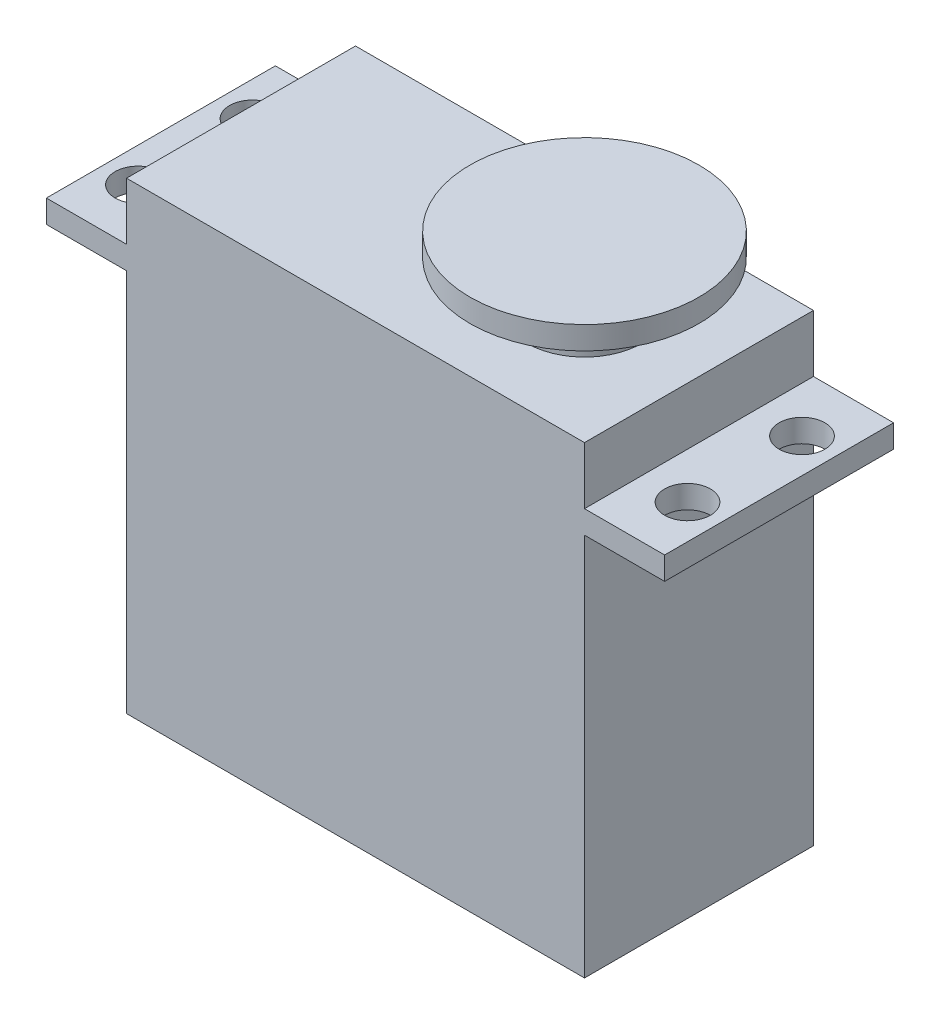
SolidWorks part; units mm, degrees
ref_plane "Front Plane" through (0, 0, 0) normal (0, 0, 1) x (1, 0, 0)
ref_plane "Top Plane" through (0, 0, 0) normal (0, 1, 0) x (1, 0, 0)
ref_plane "Right Plane" through (0, 0, 0) normal (1, 0, 0) x (0, 0, -1)
sketch "Sketch1" plane through (0, 0, 0) normal (0, 0, 1) x (1, 0, 0)
  line L1 (0, 0) -> (40, 0)
  line L2 (0, 0) -> (0, 40.5)
  line L3 (0, 40.5) -> (40, 40.5)
  line L4 (40, 0) -> (40, 40.5)
  dimension "D1" = 40.5
  dimension "D2" = 40
extrude "Boss-Extrude1" add sketch "Sketch1" along normal blind 20
sketch "Sketch2" plane through (0, 40.5, 0) normal (0, 1, 0) x (1, 0, 0)
  line L0 (40, -20) -> (40, 0) construction
  circle A0 centre (30, -10) radius 10
  dimension "D1" = 20
extrude "Boss-Extrude2" add sketch "Sketch2" along normal blind 6
sketch "Sketch3" plane through (0, 0, 0) normal (0, -1, 0) x (-1, 0, 0)
  line L1 (0, -20) -> (0, 0) construction
  line L2 (0, -20) -> (-40, -20) construction
  circle A0 centre (-17.5, -2.5) radius 1
  circle A1 centre (-17.5, -17.5) radius 1
  circle A2 centre (-2.5, -17.5) radius 1
  circle A3 centre (-2.5, -2.5) radius 1
  dimension "D3" = 2
  dimension "D4" = 2.5
  dimension "D1" = 15
  dimension "D2" = 15
  dimension "D5" = 2.5
sketch "Sketch4" plane through (0, 40.5, 0) normal (0, 1, 0) x (1, 0, 0)
  line L0 (9.5, -17) -> (9.5, -3) construction
  line L1 (0, -20) -> (0, 0) construction
  line L2 (30, 0) -> (0, 0) construction
  circle A0 centre (2.5, -10) radius 1.0762
  circle A1 centre (9.5, -17) radius 1.0762
  circle A2 centre (9.5, -3) radius 1.0762
  dimension "D4" = 2.5
  dimension "D5" = 3
  dimension "D1" = 14
  dimension "D2" = 7
  dimension "D3" = 7
sketch "Sketch5" plane through (0, 40.5, 0) normal (0, 1, 0) x (1, 0, 0)
  circle A0 centre (30, -10) radius 10
  circle A1 centre (30, -10) radius 5
  dimension "D1" = 10
extrude "Cut-Extrude3" cut sketch "Sketch5" along normal blind 4
sketch "Sketch6" plane through (0, 0, 0) normal (-1, 0, 0) x (0, 0, 1)
  line L0 (20, 40.5) -> (20, 0) construction
  line L1 (20, 35.5) -> (0, 35.5)
  line L2 (20, 35.5) -> (20, 33.5)
  line L3 (20, 33.5) -> (0, 33.5)
  line L4 (0, 35.5) -> (0, 33.5)
  line L5 (0, 40.5) -> (0, 0) construction
  line L6 (20, 40.5) -> (0, 40.5) construction
  dimension "D1" = 5
  dimension "D2" = 2
extrude "Boss-Extrude3" add sketch "Sketch6" along normal blind 7
sketch "Sketch7" plane through (0, 35.5, 0) normal (0, 1, 0) x (1, 0, 0)
  line L0 (0, -20) -> (0, 0) construction
  line L1 (-7, -20) -> (0, -20) construction
  line L2 (-7, 0) -> (0, 0) construction
  circle A0 centre (-4, -15) radius 2
  circle A1 centre (-4, -5) radius 2
  dimension "D1" = 4
  dimension "D2" = 4
  dimension "D3" = 5
  dimension "D4" = 5
extrude "Cut-Extrude5" cut sketch "Sketch7" against normal up to surface (2 mm away) up to face at (-5.25, 33.5, 7.5)
ref_plane "Plane1" through (20, 0, 0) normal (-1, 0, 0) x (0, 0, 1)
mirror "Mirror1" about plane through (20, 0, 0) normal (-1, 0, 0) of "Cut-Extrude5", "Boss-Extrude3"
